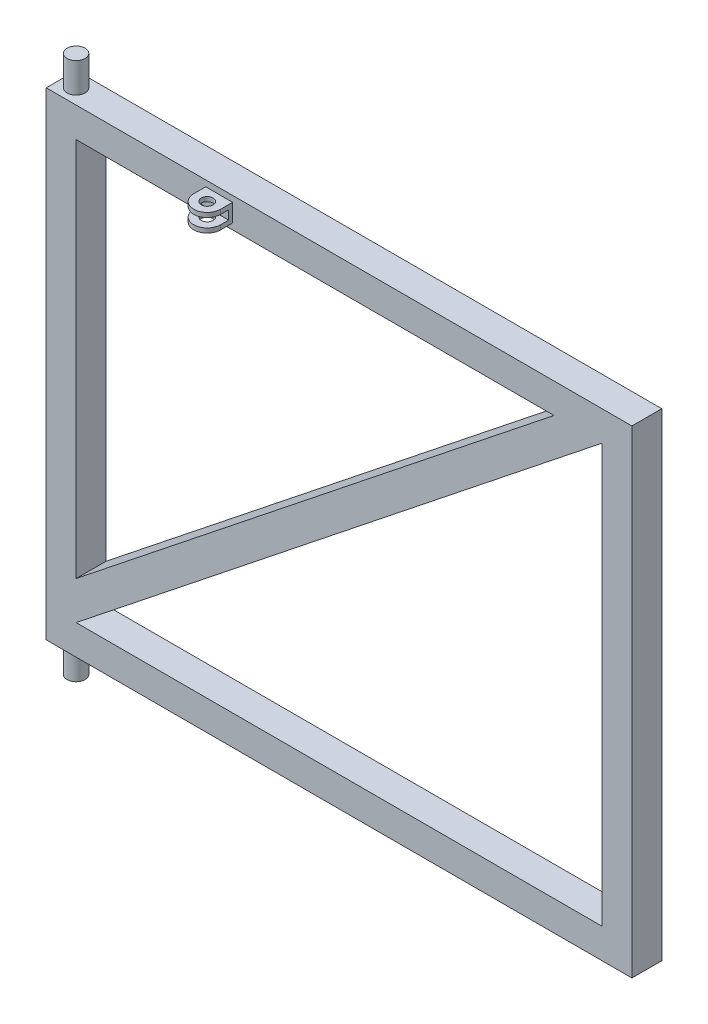
SolidWorks part; units mm, degrees
ref_plane "Plan de face" through (0, 0, 0) normal (0, 0, 1) x (1, 0, 0)
ref_plane "Plan de dessus" through (0, 0, 0) normal (0, 1, 0) x (1, 0, 0)
ref_plane "Plan de droite" through (0, 0, 0) normal (1, 0, 0) x (0, 0, -1)
sketch "Esquisse1" plane through (0, 0, 0) normal (0, 0, 1) x (1, 0, 0)
  line L1 (0, 0) -> (980, 0)
  line L2 (0, 0) -> (0, -800)
  line L3 (0, -800) -> (980, -800)
  line L4 (980, 0) -> (980, -800)
  line L8 (50, -50) -> (849.6818, -50)
  line L9 (930, -50) -> (930, -750)
  line L10 (50, -750) -> (930, -750)
  line L11 (50, -50) -> (50, -686.1105)
  line L12 (930, -50) -> (50, -750)
  line L13 (849.6818, -50) -> (50, -686.1105)
  line L15 (50, -50) -> (930, -50) construction
  line L16 (898.8738, -10.8699) -> (18.8738, -710.8699) construction
  line L17 (50, -50) -> (50, -750) construction
  dimension "D1" = 980
  dimension "D2" = 800
  dimension "D3" = 0
  dimension "D4" = 0
  dimension "D6" = 50
  dimension "D7" = 50
extrude "Boss.-Extru.1" add sketch "Esquisse1" along normal blind 50
sketch "Esquisse2" plane through (0, 0, 0) normal (0, 1, 0) x (1, 0, 0)
  line L0 (980, 0) -> (0, 0) construction
  line L1 (0, -50) -> (0, 0) construction
  circle A0 centre (25, -25) radius 15
  dimension "D1" = 25
  dimension "D2" = 30
  dimension "D3" = 25
extrude "Boss.-Extru.2" add sketch "Esquisse2" along normal blind 50
sketch "Esquisse3" plane through (0, -800, 0) normal (0, -1, 0) x (1, 0, 0)
  line L0 (0, 50) -> (980, 50) construction
  line L1 (0, 50) -> (0, 0) construction
  circle A0 centre (25, 25) radius 15.1806
  dimension "D1" = 25
  dimension "D2" = 25
extrude "Boss.-Extru.3" add sketch "Esquisse3" along normal blind 50
ref_plane "Plan1" through (0, -25, 0) normal (0, 1, 0) x (1, 0, 0)
sketch "Esquisse4" plane through (0, -25, 0) normal (0, 1, 0) x (1, 0, 0)
  line L1 (311.8283, -25.4731) -> (266.8283, -25.4731)
  line L2 (311.8283, -25.4731) -> (311.8283, -70)
  line L3 (980, -50) -> (0, -50) construction
  line L4 (266.8283, -25.4731) -> (266.8283, -70)
  arc A0 (266.8283, -70) -> (311.8283, -70) centre (289.3283, -70) ccw
  circle A1 centre (25, -25) radius 15 construction
  circle A2 centre (289.3283, -70) radius 10
  dimension "D3" = 264.3283
  dimension "D5" = 20
  dimension "D2" = 20
  dimension "D1" = 45
extrude "Boss.-Extru.4" add sketch "Esquisse4" along normal mid plane 30
sketch "Esquisse5" plane through (0, -25, 0) normal (0, 1, 0) x (1, 0, 0)
  line L1 (250.3427, -56.6013) -> (327.0135, -56.6013)
  line L2 (250.3427, -56.6013) -> (250.3427, -112.0775)
  line L3 (250.3427, -112.0775) -> (327.0135, -112.0775)
  line L4 (327.0135, -56.6013) -> (327.0135, -112.0775)
extrude "Enlèv. mat.-Extru.1" cut sketch "Esquisse5" against normal mid plane 15
